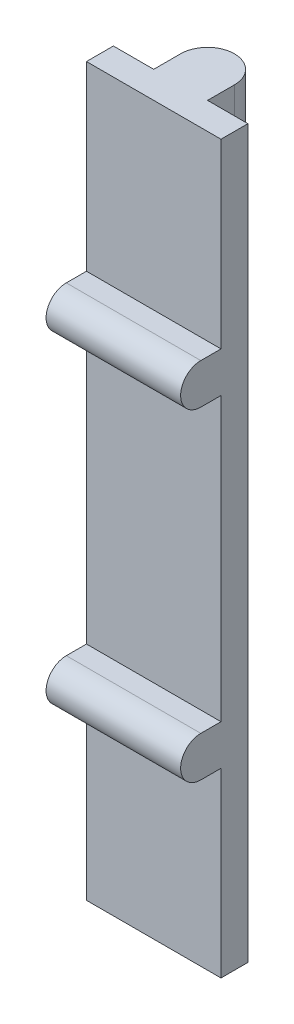
SolidWorks part; units mm, degrees
ref_plane "Front Plane" through (0, 0, 0) normal (0, 0, 1) x (1, 0, 0)
ref_plane "Top Plane" through (0, 0, 0) normal (0, 1, 0) x (1, 0, 0)
ref_plane "Right Plane" through (0, 0, 0) normal (1, 0, 0) x (0, 0, -1)
sketch "Sketch1" plane through (0, 0, 0) normal (0, 0, 1) x (1, 0, 0)
  line L1 (0, 0) -> (-127, 0)
  line L2 (0, 0) -> (0, 685.8)
  line L3 (0, 685.8) -> (-127, 685.8)
  line L4 (-127, 0) -> (-127, 685.8)
  dimension "D1" = 127
  dimension "D2" = 685.8
extrude "Boss-Extrude1" add sketch "Sketch1" along normal blind 25.4
sketch "Sketch2" plane through (-127, 0, 0) normal (-1, 0, 0) x (0, 0, 1)
  line L0 (25.4, 685.8) -> (25.4, 0) construction
  line L1 (44.45, 514.35) -> (25.4, 514.35)
  line L2 (44.45, 476.25) -> (25.4, 476.25)
  line L3 (25.4, 514.35) -> (25.4, 476.25)
  line L4 (44.45, 209.55) -> (25.4, 209.55)
  line L5 (44.45, 171.45) -> (25.4, 171.45)
  line L6 (25.4, 209.55) -> (25.4, 171.45)
  line L7 (25.4, 0) -> (0, 0) construction
  arc A0 (44.45, 171.45) -> (44.45, 209.55) centre (44.45, 190.5) ccw
  arc A1 (44.45, 476.25) -> (44.45, 514.35) centre (44.45, 495.3) ccw
  dimension "D1" = 38.1
  dimension "D2" = 190.5
  dimension "D3" = 304.8
extrude "Boss-Extrude2" add sketch "Sketch2" against normal up to surface (127 mm away) up to face at (0, 342.9, 12.7)
sketch "Sketch3" plane through (0, 0, 0) normal (0, -1, 0) x (1, 0, 0)
  line L0 (-127, 0) -> (0, 0) construction
  line L1 (-88.9, -25.4) -> (-88.9, 0)
  line L2 (-38.1, -25.4) -> (-38.1, 0)
  line L3 (-88.9, 0) -> (-38.1, 0)
  arc A0 (-88.9, -25.4) -> (-38.1, -25.4) centre (-63.5, -25.4) ccw
  point P10 (-63.5, 0)
  dimension "D1" = 50.8
extrude "Boss-Extrude3" add sketch "Sketch3" against normal up to surface (685.8 mm away) up to face at (-63.5, 685.8, 12.7)
